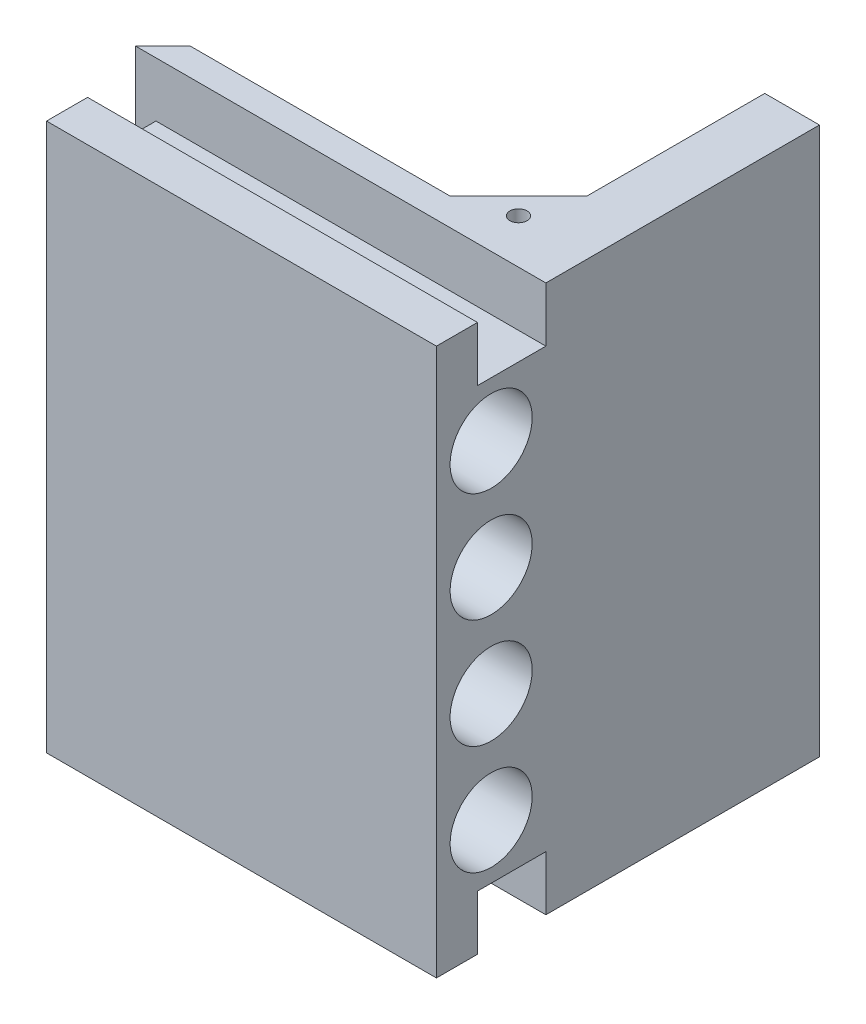
SolidWorks part; units mm, degrees
ref_plane "Front Plane" through (0, 0, 0) normal (0, 0, 1) x (1, 0, 0)
ref_plane "Top Plane" through (0, 0, 0) normal (0, 1, 0) x (1, 0, 0)
ref_plane "Right Plane" through (0, 0, 0) normal (1, 0, 0) x (0, 0, -1)
sketch "Sketch1" plane through (0, 0, 0) normal (0, 1, 0) x (1, 0, 0)
  line L0 (-17.3516, 20.3127) -> (-57.3516, -19.6873)
  line L1 (-17.3516, 20.3127) -> (2.6484, 20.3127)
  line L2 (-17.3516, 20.3127) -> (-17.3516, -19.6873)
  line L3 (-17.3516, -19.6873) -> (2.6484, -19.6873)
  line L4 (2.6484, 20.3127) -> (2.6484, -19.6873)
  line L5 (-57.3516, -19.6873) -> (-17.3516, -19.6873)
  dimension "D1" = 20
  dimension "D2" = 40
  dimension "D3" = 40
extrude "Boss-Extrude1" add sketch "Sketch1" against normal blind 80 contours L0 L5 L2 | L4 L1 L2 L3
sketch "Sketch8" plane through (2.6484, 0, 0) normal (1, 0, 0) x (0, 0, -1)
  line L0 (-19.6873, -80) -> (-19.6873, 0) construction
  line L14 (-19.6873, -8) -> (-35.6873, -8)
  line L15 (-19.6873, -8) -> (-19.6873, -72)
  line L16 (-19.6873, -72) -> (-35.6873, -72)
  line L17 (-35.6873, -8) -> (-35.6873, -72)
  dimension "D2" = 64
  dimension "D3" = 8
  dimension "D12" = 16
extrude "Boss-Extrude2" add sketch "Sketch8" against normal blind 57
sketch "Sketch12" plane through (0, -72, 0) normal (0, -1, 0) x (1, 0, 0)
  line L0 (2.6484, 35.6873) -> (2.6484, 19.6873) construction
  line L1 (-54.3516, 35.6873) -> (2.6484, 35.6873)
  line L2 (-54.3516, 35.6873) -> (-54.3516, 29.6873)
  line L3 (-54.3516, 29.6873) -> (2.6484, 29.6873)
  line L4 (2.6484, 35.6873) -> (2.6484, 29.6873)
  dimension "D1" = 6
sketch "Sketch10" plane through (2.6484, 0, 0) normal (1, 0, 0) x (0, 0, -1)
  line L8 (-27.6873, -8) -> (-27.6873, -72) construction
  line L9 (-19.6873, -8) -> (-35.6873, -8) construction
  line L10 (-35.6873, -72) -> (-19.6873, -72) construction
  circle A0 centre (-27.6873, -16) radius 6
  circle A4 centre (-27.6873, -32) radius 6
  circle A5 centre (-27.6873, -64) radius 6
  circle A6 centre (-27.6873, -48) radius 6
  dimension "D1" = 12
  dimension "D2" = 8
extrude "Cut-Extrude1" cut sketch "Sketch10" against normal blind 51
extrude "Boss-Extrude3" add sketch "Sketch12" along normal blind 8
sketch "Sketch14" plane through (0, -8, 0) normal (0, 1, 0) x (1, 0, 0)
  line L0 (2.6484, -19.6873) -> (2.6484, -35.6873) construction
  line L1 (-54.3516, -35.6873) -> (2.6484, -35.6873)
  line L2 (-54.3516, -35.6873) -> (-54.3516, -29.6873)
  line L3 (-54.3516, -29.6873) -> (2.6484, -29.6873)
  line L4 (2.6484, -35.6873) -> (2.6484, -29.6873)
  dimension "D1" = 6
extrude "Boss-Extrude4" add sketch "Sketch14" along normal blind 8
sketch "Sketch17" plane through (0, 0, -20.3127) normal (0, 0, -1) x (-1, 0, 0)
  line L1 (5.3516, 0) -> (53.3516, 0)
  line L2 (5.3516, 0) -> (5.3516, -80)
  line L3 (5.3516, -80) -> (53.3516, -80)
  line L4 (53.3516, 0) -> (53.3516, -80)
  line L6 (57.3516, -80) -> (57.3516, 0) construction
  line L7 (-2.6484, -80) -> (-2.6484, 0) construction
  line L8 (17.3516, 0) -> (57.3516, 0) construction
  line L9 (17.3516, -80) -> (57.3516, -80) construction
  dimension "D3" = 4
  dimension "D4" = 8
extrude "Cut-Extrude4" cut sketch "Sketch17" against normal blind 36
chamfer "Chamfer1" distance 10 angle 45 1 edges at (-5.3516, -40, 15.6873)
sketch "Sketch16" plane through (0, 0, 15.6873) normal (0, 0, -1) x (-1, 0, 0)
  line L0 (53.3516, -80) -> (53.3516, 0) construction
  line L1 (53.3516, -76) -> (5.3516, -76)
  line L2 (53.3516, -76) -> (53.3516, -4)
  line L3 (53.3516, -4) -> (5.3516, -4)
  line L4 (5.3516, -76) -> (5.3516, -4)
  line L5 (5.3516, 0) -> (5.3516, -80) construction
  line L6 (53.3516, 0) -> (15.3516, 0) construction
  line L7 (15.3516, -80) -> (53.3516, -80) construction
  dimension "D1" = 4
  dimension "D2" = 4
extrude "Cut-Extrude5" cut sketch "Sketch16" along normal blind 10
sketch "Sketch19" plane through (0, 0, 0) normal (0, 1, 0) x (1, 0, 0)
  line L0 (-15.3516, -15.6873) -> (2.6484, -15.6873) construction
  line L1 (-5.3516, -5.6873) -> (-15.3516, -15.6873) construction
  line L2 (2.6484, 20.3127) -> (2.6484, -19.6873) construction
  line L3 (-5.3516, -5.6873) -> (-5.3516, -19.6873) construction
  line L4 (-57.3516, -19.6873) -> (2.6484, -19.6873) construction
  line L5 (-10.3516, -10.6873) -> (-5.3516, -15.6873) construction
  circle A0 centre (-7.8516, -13.1873) radius 1.25
  point P15 (0, 0)
  point P16 (-6.3225, -12.022)
  point P17 (-7.8516, -13.1873)
  dimension "D1" = 2.5
extrude "Cut-Extrude6" cut sketch "Sketch19" against normal through all
